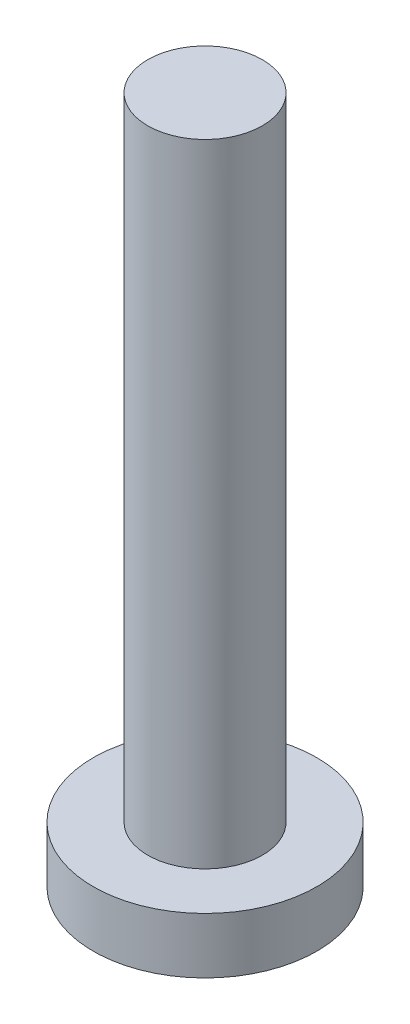
SolidWorks part; units mm, degrees
ref_plane "Front Plane" through (0, 0, 0) normal (0, 0, 1) x (1, 0, 0)
ref_plane "Top Plane" through (0, 0, 0) normal (0, 1, 0) x (1, 0, 0)
ref_plane "Right Plane" through (0, 0, 0) normal (1, 0, 0) x (0, 0, -1)
sketch "Sketch1" plane through (0, 0, 0) normal (0, 1, 0) x (1, 0, 0)
  circle A0 centre (0, 0) radius 1.025
  dimension "D1" = 2.05
extrude "Boss-Extrude1" add sketch "Sketch1" along normal blind 11.3
sketch "Sketch2" plane through (0, 0, 0) normal (0, -1, 0) x (1, 0, 0)
  circle A0 centre (0, 0) radius 2
extrude "Boss-Extrude2" add sketch "Sketch2" along normal blind 1
